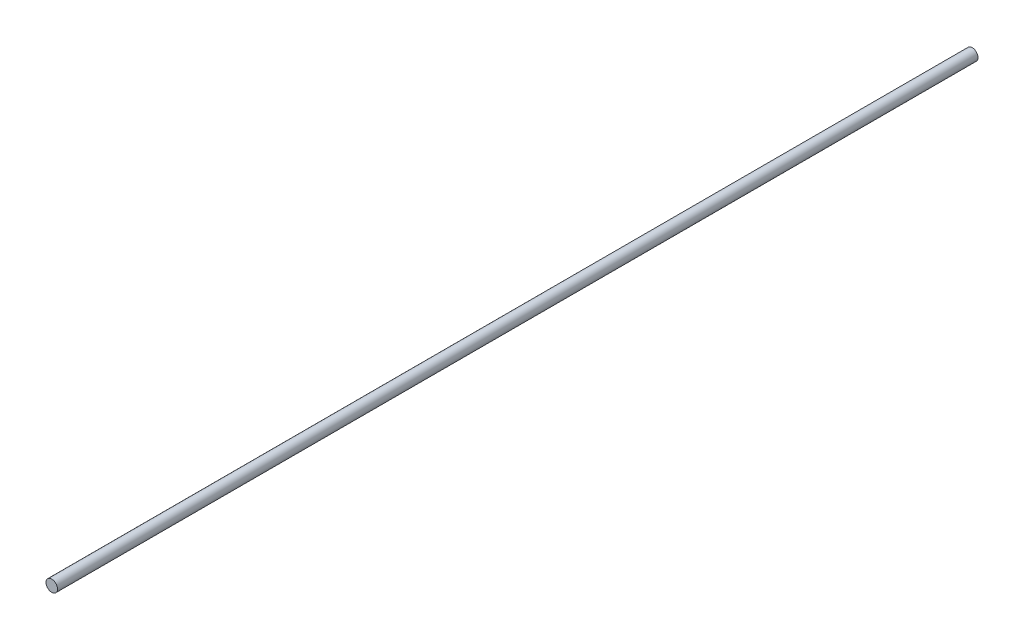
SolidWorks part; units mm, degrees
material "Pine"
ref_plane "Front Plane" through (0, 0, 0) normal (0, 0, 1) x (1, 0, 0)
ref_plane "Top Plane" through (0, 0, 0) normal (0, 1, 0) x (1, 0, 0)
ref_plane "Right Plane" through (0, 0, 0) normal (1, 0, 0) x (0, 0, -1)
sketch "Sketch1" plane through (0, 0, 0) normal (0, 0, 1) x (1, 0, 0)
  circle A0 centre (0, 0) radius 3.175
  dimension "D1" = 6.35
extrude "Boss-Extrude1" add sketch "Sketch1" along normal mid plane 508
